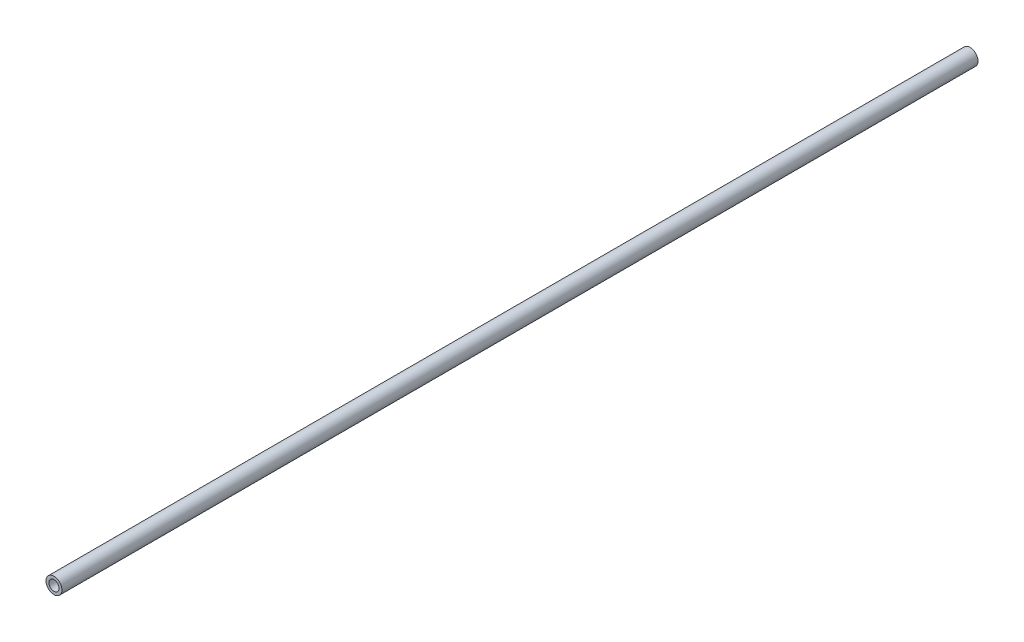
SolidWorks part; units mm, degrees
ref_plane "Front Plane" through (0, 0, 0) normal (0, 0, 1) x (1, 0, 0)
ref_plane "Top Plane" through (0, 0, 0) normal (0, 1, 0) x (1, 0, 0)
ref_plane "Right Plane" through (0, 0, 0) normal (1, 0, 0) x (0, 0, -1)
sketch "Sketch1" plane through (0, 0, 0) normal (0, 0, 1) x (1, 0, 0)
  circle A0 centre (0, 0) radius 2.75
  circle A1 centre (0, 0) radius 1.75
  dimension "D1" = 3.5
  dimension "D2" = 5.5
extrude "Boss-Extrude1" add sketch "Sketch1" along normal blind 316
